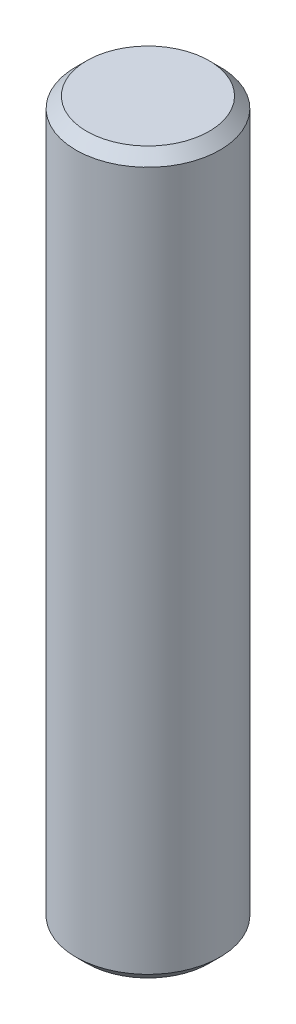
SolidWorks part; units mm, degrees
ref_plane "前视基准面" through (0, 0, 0) normal (0, 0, 1) x (1, 0, 0)
ref_plane "上视基准面" through (0, 0, 0) normal (0, 1, 0) x (1, 0, 0)
ref_plane "右视基准面" through (0, 0, 0) normal (1, 0, 0) x (0, 0, -1)
sketch "草图1" plane through (0, 0, 0) normal (0, 1, 0) x (1, 0, 0)
  circle A0 centre (0, 0) radius 2
  dimension "D1" = 4
extrude "凸台-拉伸1" add sketch "草图1" along normal blind 20
chamfer "倒角1" distance 0.3 angle 45 2 edges at (0, 20, 2) (0, 0, 2)
